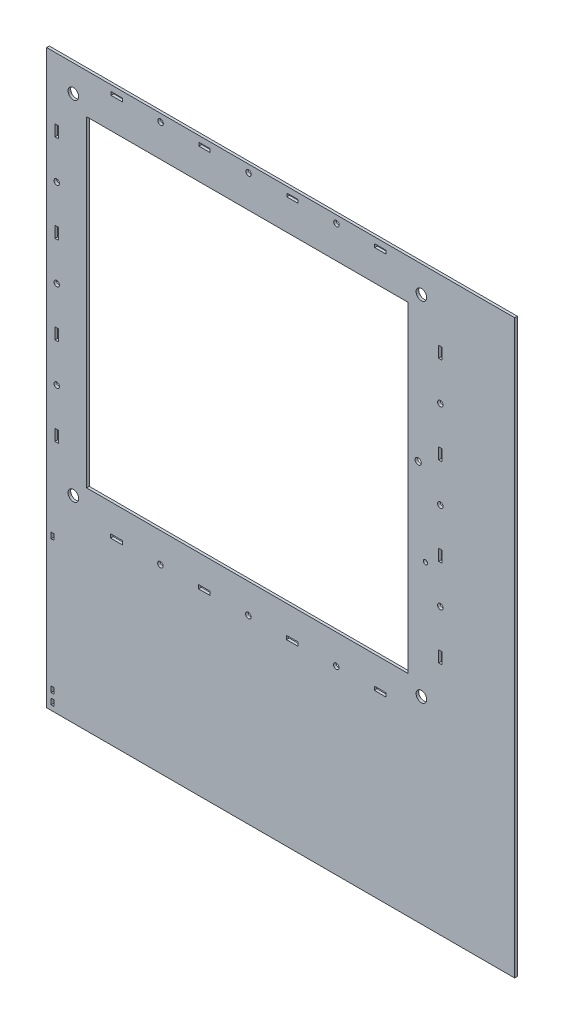
SolidWorks part; units mm, degrees
ref_plane "前视基准面" through (0, 0, 0) normal (0, 0, 1) x (1, 0, 0)
ref_plane "上视基准面" through (0, 0, 0) normal (0, 1, 0) x (1, 0, 0)
ref_plane "右视基准面" through (0, 0, 0) normal (1, 0, 0) x (0, 0, -1)
sketch "草图1" plane through (0, 0, 0) normal (0, 0, 1) x (1, 0, 0)
  line L0 (95.3243, -141.495) -> (104.1243, -141.495)
  line L1 (0.7243, -148.895) -> (0.7243, -142.895) construction
  line L2 (0.7243, -142.895) -> (33.7243, -142.895) construction
  line L3 (33.7243, -142.895) -> (66.7243, -142.895) construction
  line L4 (29.3243, -141.495) -> (38.1243, -141.495)
  line L5 (29.3243, -141.495) -> (29.3243, -144.295)
  line L6 (29.3243, -144.295) -> (38.1243, -144.295)
  line L7 (38.1243, -141.495) -> (38.1243, -144.295)
  line L8 (29.3243, -141.495) -> (38.1243, -144.295) construction
  line L9 (29.3243, -144.295) -> (38.1243, -141.495) construction
  line L10 (66.7243, -142.895) -> (99.7243, -142.895) construction
  line L11 (95.3243, -141.495) -> (95.3243, -144.295)
  line L12 (95.3243, -144.295) -> (104.1243, -144.295)
  line L13 (95.3243, -144.295) -> (104.1243, -141.495) construction
  line L14 (104.1243, -144.295) -> (104.1243, -141.495)
  line L15 (-36.6757, -141.495) -> (-36.6757, -144.295)
  line L16 (-27.8757, -141.495) -> (-36.6757, -141.495)
  line L17 (-27.8757, -141.495) -> (-27.8757, -144.295)
  line L18 (-27.8757, -144.295) -> (-36.6757, -144.295)
  line L19 (-93.8757, -141.495) -> (-93.8757, -144.295)
  line L20 (-102.6757, -144.295) -> (-102.6757, -141.495)
  line L21 (-93.8757, -141.495) -> (-102.6757, -141.495)
  line L22 (-93.8757, -144.295) -> (-102.6757, -144.295)
  line L23 (-141.8757, 95.705) -> (-141.8757, 104.205)
  line L24 (-144.3757, 95.705) -> (-144.3757, 104.205)
  line L25 (-144.3757, 104.205) -> (-141.8757, 104.205)
  line L26 (-141.8757, 95.705) -> (-144.3757, 95.705)
  line L27 (-141.8757, 29.705) -> (-141.8757, 38.205)
  line L28 (-141.8757, 38.205) -> (-144.3757, 38.205)
  line L29 (-144.3757, 29.705) -> (-144.3757, 38.205)
  line L30 (-141.8757, 29.705) -> (-144.3757, 29.705)
  line L31 (-141.8757, -27.795) -> (-144.3757, -27.795)
  line L32 (-141.8757, -27.795) -> (-141.8757, -36.295)
  line L33 (-144.3757, -27.795) -> (-144.3757, -36.295)
  line L34 (-141.8757, -36.295) -> (-144.3757, -36.295)
  line L35 (-141.8757, -93.795) -> (-141.8757, -102.295)
  line L36 (-144.3757, -93.795) -> (-144.3757, -102.295)
  line L37 (-141.8757, -93.795) -> (-144.3757, -93.795)
  line L38 (-144.3757, -102.295) -> (-141.8757, -102.295)
  line L39 (95.6243, 143.705) -> (104.1243, 143.705)
  line L40 (95.6243, 146.205) -> (104.1243, 146.205)
  line L41 (104.1243, 146.205) -> (104.1243, 143.705)
  line L42 (95.6243, 143.705) -> (95.6243, 146.205)
  line L43 (29.6243, 143.705) -> (38.1243, 143.705)
  line L44 (38.1243, 143.705) -> (38.1243, 146.205)
  line L45 (29.6243, 146.205) -> (38.1243, 146.205)
  line L46 (29.6243, 143.705) -> (29.6243, 146.205)
  line L47 (-27.8757, 143.705) -> (-27.8757, 146.205)
  line L48 (-27.8757, 143.705) -> (-36.3757, 143.705)
  line L49 (-27.8757, 146.205) -> (-36.3757, 146.205)
  line L50 (-36.3757, 143.705) -> (-36.3757, 146.205)
  line L51 (-93.8757, 143.705) -> (-102.3757, 143.705)
  line L52 (-93.8757, 146.205) -> (-102.3757, 146.205)
  line L53 (-93.8757, 143.705) -> (-93.8757, 146.205)
  line L54 (-102.3757, 146.205) -> (-102.3757, 143.705)
  line L55 (143.6243, -93.795) -> (143.6243, -102.295)
  line L56 (146.1243, -93.795) -> (146.1243, -102.295)
  line L57 (146.1243, -102.295) -> (143.6243, -102.295)
  line L58 (143.6243, -93.795) -> (146.1243, -93.795)
  line L59 (143.6243, -27.795) -> (143.6243, -36.295)
  line L60 (143.6243, -36.295) -> (146.1243, -36.295)
  line L61 (146.1243, -27.795) -> (146.1243, -36.295)
  line L62 (143.6243, -27.795) -> (146.1243, -27.795)
  line L63 (143.6243, 29.705) -> (146.1243, 29.705)
  line L64 (143.6243, 29.705) -> (143.6243, 38.205)
  line L65 (146.1243, 29.705) -> (146.1243, 38.205)
  line L66 (143.6243, 38.205) -> (146.1243, 38.205)
  line L67 (143.6243, 95.705) -> (143.6243, 104.205)
  line L68 (146.1243, 95.705) -> (146.1243, 104.205)
  line L69 (143.6243, 95.705) -> (146.1243, 95.705)
  line L70 (146.1243, 104.205) -> (143.6243, 104.205)
  line L71 (50.2243, -142.895) -> (50.2243, -127.895) construction
  line L72 (17.2243, -142.895) -> (17.2243, -127.895) construction
  line L73 (120.6507, 120.6507) -> (-120.6507, 120.6507)
  line L75 (99.7243, -142.895) -> (104.1243, -144.295) construction
  line L76 (150.6507, -150.6507) -> (150.6507, 150.6507) construction
  line L78 (-150.6507, -150.6507) -> (-150.6507, 150.6507)
  line L79 (150.6507, -150.6507) -> (-150.6507, 150.6507) construction
  line L80 (150.6507, 150.6507) -> (-150.6507, -150.6507) construction
  line L81 (-120.6507, -120.6507) -> (-120.6507, 120.6507)
  line L82 (120.6507, -120.6507) -> (-120.6507, -120.6507)
  line L83 (120.6507, -120.6507) -> (120.6507, 120.6507)
  line L84 (-150.6507, 150.6507) -> (-150.6507, 277.9507) construction
  line L85 (-150.6507, 277.9507) -> (150.6507, 277.9507) construction
  line L86 (150.6507, 277.9507) -> (150.6507, 150.6507) construction
  line L87 (150.6507, 150.6507) -> (-150.6507, 150.6507)
  line L88 (150.6507, 150.6507) -> (-150.6507, 150.6507) construction
  line L89 (-120.6507, 180.6507) -> (-120.6507, 247.9507) construction
  line L90 (-120.6507, 247.9507) -> (120.6507, 247.9507) construction
  line L91 (120.6507, 247.9507) -> (120.6507, 180.6507) construction
  line L92 (120.6507, 180.6507) -> (-120.6507, 180.6507) construction
  line L93 (120.6507, -180.6507) -> (120.6507, -248.6507) construction
  line L94 (-150.6507, -150.6507) -> (150.6507, -150.6507) construction
  line L95 (-150.6507, -150.6507) -> (-150.6507, -278.6507)
  line L96 (-150.6507, -278.6507) -> (150.6507, -278.6507)
  line L97 (150.6507, -150.6507) -> (150.6507, -278.6507) construction
  line L98 (150.6507, -150.6507) -> (-150.6507, -150.6507) construction
  line L99 (-120.6507, -248.6507) -> (120.6507, -248.6507) construction
  line L100 (-120.6507, -180.6507) -> (-120.6507, -248.6507) construction
  line L101 (-120.6507, -180.6507) -> (120.6507, -180.6507) construction
  line L103 (150.6507, 150.6507) -> (200.6507, 150.6507)
  line L106 (200.6507, 150.6507) -> (200.6507, -278.6507)
  line L110 (200.8743, -261.0808) -> (200.6507, -261.0808)
  line L115 (-145.0257, -270.745) -> (-147.3257, -270.745)
  line L116 (-145.0257, -270.745) -> (-145.0257, -275.045)
  line L117 (-145.0257, -275.045) -> (-147.3257, -275.045)
  line L118 (-147.3257, -270.745) -> (-147.3257, -275.045)
  line L119 (-145.0257, -262.745) -> (-147.3257, -262.745)
  line L120 (-145.0257, -262.745) -> (-145.0257, -267.045)
  line L121 (-145.0257, -267.045) -> (-147.3257, -267.045)
  line L122 (-147.3257, -262.745) -> (-147.3257, -267.045)
  line L123 (150.6507, -278.6507) -> (200.6507, -278.6507)
  line L125 (-145.0257, -162.745) -> (-147.3257, -162.745)
  line L126 (-145.0257, -162.745) -> (-145.0257, -167.045)
  line L127 (-145.0257, -167.045) -> (-147.3257, -167.045)
  line L128 (-147.3257, -162.745) -> (-147.3257, -167.045)
  circle A0 centre (0.7243, -142.895) radius 2.05
  circle A1 centre (66.7243, -142.895) radius 2.05
  circle A2 centre (-65.2757, -142.895) radius 2.05
  circle A3 centre (-143.1257, 66.955) radius 2.05
  circle A4 centre (-143.1257, 0.955) radius 2.05
  circle A5 centre (-143.1257, -65.045) radius 2.05
  circle A6 centre (66.8743, 144.955) radius 2.05
  circle A7 centre (0.8743, 144.955) radius 2.05
  circle A8 centre (-65.1257, 144.955) radius 2.05
  circle A9 centre (144.8743, -65.045) radius 2.05
  circle A10 centre (144.8743, 0.955) radius 2.05
  circle A11 centre (144.8743, 66.955) radius 2.05
  circle A12 centre (-130.6507, -130.6507) radius 4
  circle A18 centre (-130.6507, 130.6507) radius 4
  circle A19 centre (130.6507, 130.6507) radius 4
  circle A20 centre (130.6507, -130.6507) radius 4
  circle A21 centre (128.2349, 21.0459) radius 2.333
  circle A22 centre (133.7092, -41.7691) radius 1.6011
  point P25 (0, 0)
  dimension "D4" = 66
  dimension "D5" = 33
  dimension "D6" = 4.1
  dimension "D9" = 30
  dimension "D13" = 8
  dimension "D1" = 8.8
  dimension "D2" = 2.8
  dimension "D3" = 30
  dimension "D7" = 8.8
  dimension "D8" = 2.8
  dimension "D11" = 127.3
  dimension "D10" = 301.3014
  dimension "D14" = 4
  dimension "D15" = 128
  dimension "D16" = 50
  dimension "D12" = 30
extrude "凸台-拉伸1" add sketch "草图1" along normal blind 2
